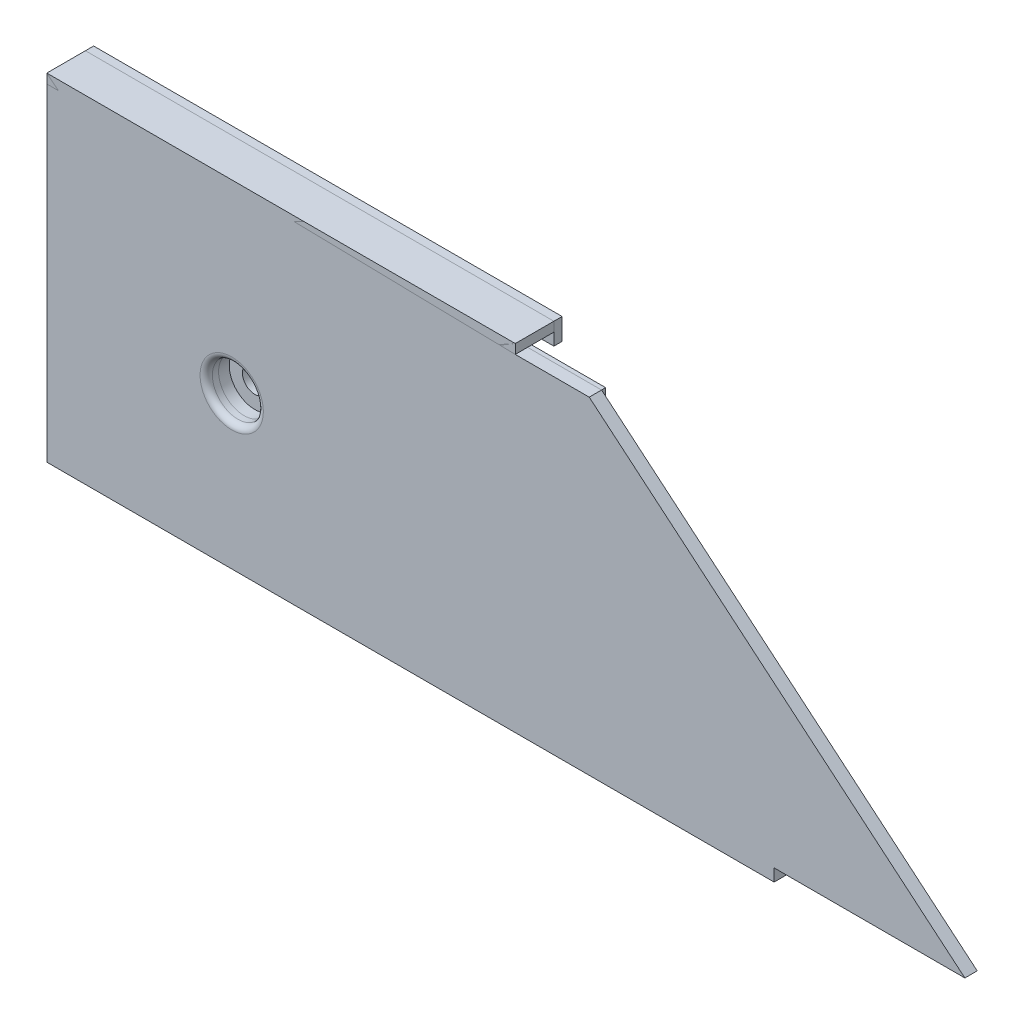
SolidWorks part; units mm, degrees
ref_plane "Спереди" through (0, 0, 0) normal (0, 0, 1) x (1, 0, 0)
ref_plane "Сверху" through (0, 0, 0) normal (0, 1, 0) x (1, 0, 0)
ref_plane "Справа" through (0, 0, 0) normal (1, 0, 0) x (0, 0, -1)
sketch "Эскиз2" plane through (0, 0, 0) normal (0, 0, 1) x (1, 0, 0)
  line L0 (-45.1615, 41.0019) -> (-45.1615, 39.8528) construction
  line L1 (-46.1615, 31.0019) -> (-113.1615, 31.0019) construction
  line L2 (-47.6615, 32.1019) -> (-113.1615, 32.1019) construction
  line L3 (-113.1615, 32.1019) -> (-113.1615, 31.0019) construction
  line L4 (-46.1615, 41.0019) -> (-46.1615, 31.0019) construction
  line L5 (-47.6615, 41.0019) -> (-47.6615, 32.1019) construction
  line L6 (-45.1615, 31.0019) -> (-46.6615, 31.0019) construction
  line L7 (-47.6615, 41.0019) -> (-47.6615, 32.1019) construction
  line L8 (-13.6668, 0) -> (13.6668, 0) construction
  line L9 (13.6668, 0) -> (-35.1974, 41.0019) construction
  line L10 (-35.1974, 41.0019) -> (-45.1615, 41.0019) construction
  line L11 (-13.6668, 0) -> (-13.6668, 1.5)
  line L12 (-13.6668, 1.5) -> (9.5456, 1.5)
  line L13 (-45.1615, 41.0019) -> (-45.1615, 39.8528)
  line L14 (9.5456, 1.5) -> (-36.1615, 39.8528)
  line L15 (-45.1615, 39.8528) -> (-36.1615, 39.8528)
  line L16 (-45.1615, 41.0019) -> (-100.1615, 41.0019)
  line L17 (-99.1615, 0) -> (-99.1615, 41.0019) construction
  line L18 (-99.1615, 0) -> (-13.6668, 0)
  line L19 (-45.1615, 41.0019) -> (-45.1615, 31.0019) construction
  line L24 (-99.1615, 0) -> (-102.1615, 0)
  line L26 (-100.1615, 41.0019) -> (-102.1615, 41.0019)
  line L27 (-102.1615, 0) -> (-102.1615, 41.0019)
  circle A0 centre (-79.6615, 18.5) radius 3.1
  circle A1 centre (-79.6615, 18.5) radius 2.5 construction
  circle A2 centre (-79.6615, 18.5) radius 1 construction
  point P0 (-45.1615, 31.0019)
  point P1 (-46.6615, 41.0019)
  point P3 (-79.6615, 31.0019)
  point P4 (-46.6615, 32.1019)
  point P5 (-52.1115, 32.1019)
  point P7 (-100.1615, 22.1019)
  point P8 (-79.6615, 21)
  point P12 (0, 0)
  point P13 (12.7026, -1.1491)
  point P19 (-104.982, 32.1019)
  point P23 (-79.6615, 16)
  point P24 (-70.2641, 31.0019)
  dimension "D7" = 4.45
  dimension "D15" = 6.2
  dimension "D19" = 5
  dimension "D20" = 2
  dimension "D3" = 1.5
  dimension "D4" = 40
  dimension "D5" = 1
  dimension "D6" = 21
  dimension "D8" = 1.5
  dimension "D9" = 67
  dimension "D10" = 23.2124
  dimension "D11" = 27.3336
  dimension "D12" = 0
  dimension "D13" = 55
  dimension "D14" = 0
  dimension "D18" = 3
extrude "Бобышка-Вытянуть11" add sketch "Эскиз2" along normal blind 1.5 separate body
sketch "Эскиз6" plane through (0, 0, 0) normal (0, 0, -1) x (-1, 0, 0)
  circle A0 centre (79.6615, 18.5) radius 3.4
  dimension "D1" = 6.8
extrude "Бобышка-Вытянуть12" add sketch "Эскиз6" along normal blind 3 separate body
sketch "Эскиз7" plane through (0, 0, 1.5) normal (0, 0, 1) x (1, 0, 0)
  line L1 (-45.1615, 39.8528) -> (-102.1615, 39.8528)
  line L2 (-45.1615, 39.8528) -> (-45.1615, 41.0019)
  line L3 (-45.1615, 41.0019) -> (-102.1615, 41.0019)
  line L4 (-102.1615, 39.8528) -> (-102.1615, 41.0019)
extrude "Бобышка-Вытянуть13" add sketch "Эскиз7" against normal blind 4.7 separate body
sketch "Эскиз10" plane through (0, 0, 0) normal (0, 0, -1) x (-1, 0, 0)
  line L1 (45.1615, 39.8528) -> (36.1615, 39.8528)
  line L2 (45.1615, 39.8528) -> (45.1615, 38.3528)
  line L3 (45.1615, 38.3528) -> (36.1615, 38.3528)
  line L4 (36.1615, 39.8528) -> (36.1615, 38.3528)
  point P0 (36.1615, 39.8528)
  point P1 (45.1615, 39.8528)
  dimension "D1" = 1.5
extrude "Бобышка-Вытянуть15" add sketch "Эскиз10" along normal blind 0.5 separate body
sketch "Эскиз11" plane through (0, 0, -3.2) normal (0, 0, -1) x (-1, 0, 0)
  line L0 (102.1615, 41.0019) -> (102.1615, 0) construction
  line L1 (45.1615, 41.0019) -> (102.1615, 41.0019)
  line L2 (45.1615, 41.0019) -> (45.1615, 38.3715)
  line L3 (45.1615, 38.3715) -> (102.1615, 38.3715)
  line L4 (102.1615, 41.0019) -> (102.1615, 38.3715)
extrude "Бобышка-Вытянуть17" add sketch "Эскиз11" along normal blind 1 separate body
sketch "Эскиз13" plane through (0, 0, 0) normal (0, 0, 1) x (1, 0, 0)
  circle A0 centre (-79.6615, 18.5) radius 3.1 construction
  circle A1 centre (-79.6615, 18.5) radius 1.5
  point P0 (-79.6615, 15.4)
  point P1 (-76.5615, 18.5)
  point P4 (-79.6615, 18.5)
  dimension "D1" = 3
extrude "Вырез-Вытянуть1" cut sketch "Эскиз13" against normal blind 3
sketch "Эскиз14" plane through (0, 0, 1.5) normal (0, 0, 1) x (1, 0, 0)
  circle A0 centre (-79.6615, 18.5) radius 3.1
extrude "Вырез-Вытянуть2" cut sketch "Эскиз14" against normal blind 2.8
fillet "Скругление1" radius 0.75 1 edges at (-76.5615, 18.5, 1.5)
